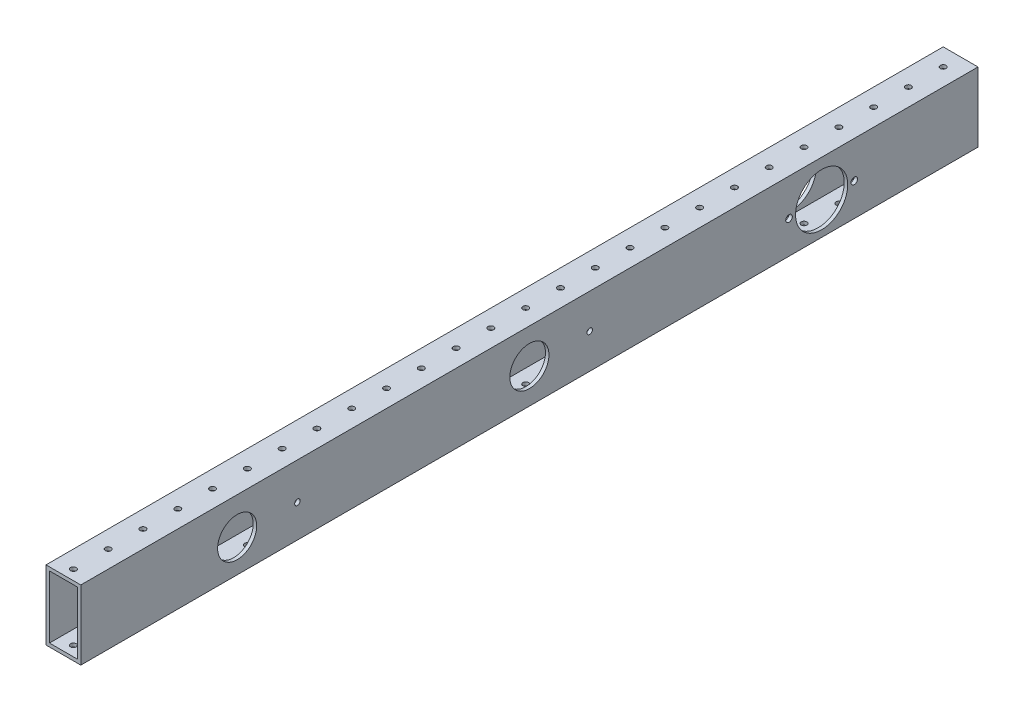
SolidWorks part; units mm, degrees
ref_plane "Alzado" through (0, 0, 0) normal (0, 0, 1) x (1, 0, 0)
ref_plane "Planta" through (0, 0, 0) normal (0, 1, 0) x (1, 0, 0)
ref_plane "Vista lateral" through (0, 0, 0) normal (1, 0, 0) x (0, 0, -1)
sketch "Croquis1" plane through (0, 0, 0) normal (0, 0, 1) x (1, 0, 0)
  line L1 (-12.7, 25.35) -> (12.7, 25.35)
  line L2 (-12.7, 25.35) -> (-12.7, -25.35)
  line L3 (-12.7, -25.35) -> (12.7, -25.35)
  line L4 (12.7, 25.35) -> (12.7, -25.35)
  line L5 (-12.7, 25.35) -> (12.7, -25.35) construction
  line L6 (-12.7, -25.35) -> (12.7, 25.35) construction
  line L7 (-10.16, 22.81) -> (10.16, 22.81)
  line L8 (-10.16, 22.81) -> (-10.16, -22.81)
  line L9 (-10.16, -22.81) -> (10.16, -22.81)
  line L10 (10.16, 22.81) -> (10.16, -22.81)
  line L11 (-10.16, 22.81) -> (10.16, -22.81) construction
  line L12 (-10.16, -22.81) -> (10.16, 22.81) construction
  point P0 (0, 0)
  point P6 (0, 0)
  dimension "D1" = 25.4
  dimension "D2" = 50.7
  dimension "D3" = 2.54
  dimension "D4" = 2.54
extrude "Saliente-Extruir1" add sketch "Croquis1" along normal blind 655
sketch "Croquis2" plane through (0, 25.35, 0) normal (0, 1, 0) x (1, 0, 0)
  line L0 (-12.7, 0) -> (12.7, 0)
  line L1 (12.7, 0) -> (0, 0)
  line L2 (0, 0) -> (0, -655)
  line L3 (12.7, -655) -> (-12.7, -655) construction
  circle A0 centre (0, -12.7) radius 2.07
  circle A1 centre (0, -38.1) radius 2.07
  circle A2 centre (0, -63.5) radius 2.07
  circle A3 centre (0, -88.9) radius 2.07
  circle A4 centre (0, -114.3) radius 2.07
  circle A5 centre (0, -139.7) radius 2.07
  circle A6 centre (0, -165.1) radius 2.07
  circle A7 centre (0, -190.5) radius 2.07
  circle A8 centre (0, -215.9) radius 2.07
  circle A9 centre (0, -241.3) radius 2.07
  circle A10 centre (0, -266.7) radius 2.07
  circle A11 centre (0, -292.1) radius 2.07
  circle A12 centre (0, -317.5) radius 2.07
  circle A13 centre (0, -342.9) radius 2.07
  circle A14 centre (0, -368.3) radius 2.07
  circle A15 centre (0, -393.7) radius 2.07
  circle A16 centre (0, -419.1) radius 2.07
  circle A17 centre (0, -444.5) radius 2.07
  circle A18 centre (0, -469.9) radius 2.07
  circle A19 centre (0, -495.3) radius 2.07
  circle A20 centre (0, -520.7) radius 2.07
  circle A21 centre (0, -546.1) radius 2.07
  circle A22 centre (0, -571.5) radius 2.07
  circle A23 centre (0, -596.9) radius 2.07
  circle A24 centre (0, -622.3) radius 2.07
  circle A25 centre (0, -647.7) radius 2.07
  dimension "D1" = 4.14
  dimension "D2" = 12.7
  dimension "D3" = 26
extrude "Cortar-Extruir1" cut sketch "Croquis2" against normal through all contours A0 | A1 | A2 | A3 | A4 | A5 | A6 | A7 | A8 | A9 | A10 | A11 | A12 | A13 | A14 | A15 | A16 | A17 | A18 | A19 | A20 | A21 | A22 | A23 | A24 | A25
sketch "Croquis3" plane through (-12.7, 0, 0) normal (-1, 0, 0) x (0, 0, 1)
  line L0 (0, 0) -> (327.5, 0)
  circle A0 centre (327.5, 0) radius 14.275
  dimension "D2" = 28.55
  dimension "D1" = 327.5
extrude "Cortar-Extruir2" cut sketch "Croquis3" against normal blind 700 contours A0
sketch "Croquis4" plane through (-12.7, 0, 0) normal (-1, 0, 0) x (0, 0, 1)
  circle A0 centre (303.9553, 0) radius 2.41
  dimension "D1" = 4.82
sketch "Croquis5" plane through (-12.7, 0, 0) normal (-1, 0, 0) x (0, 0, 1)
  line L0 (327.5, -25.35) -> (327.5926, 25.3498)
  line L2 (655, -25.35) -> (0, -25.35) construction
  line L3 (327.5926, 25.3498) -> (351.3125, 25.3498)
  line L4 (351.3125, 25.3498) -> (351.3125, -25.35)
  line L5 (351.3125, -25.35) -> (302.5949, -25.35)
  line L6 (302.5949, -25.35) -> (302.5949, 25.3498)
  line L7 (302.5949, 25.3498) -> (327.5926, 25.3498)
  line L8 (327.5, -25.35) -> (327.5463, -0.0001)
  line L9 (327.5463, -0.0001) -> (367.7335, -0.0735)
  line L10 (367.7335, -0.0735) -> (294.1923, 0.0608)
  circle A0 centre (351.3125, 0) radius 3.1556
sketch "Croquis6" plane through (-12.7, 0, 0) normal (-1, 0, 0) x (0, 0, 1)
  line L0 (82.895, 0) -> (478.5071, 0)
  circle A1 centre (303.6875, 0) radius 2.41
  circle A2 centre (351.3125, 0) radius 2.41
  circle A3 centre (354.42, 1.3931) radius 0.0224
  dimension "D1" = 4.82
sketch "Croquis7" plane through (-12.7, 0, 0) normal (-1, 0, 0) x (0, 0, 1)
  circle A0 centre (114.1451, -1.474) radius 14.2748
sketch "Croquis8" plane through (-12.7, 0, 0) normal (-1, 0, 0) x (0, 0, 1)
  circle A0 centre (114.1451, -1.474) radius 19.05
  circle A1 centre (540.8549, -1.474) radius 14.2748
  dimension "D1" = 28.5496
  dimension "D2" = 38.1
extrude "Cortar-Extruir5" cut sketch "Croquis8" against normal blind 700
sketch "Croquis9" plane through (-12.7, 0, 0) normal (-1, 0, 0) x (0, 0, 1)
  line L1 (655, 25.35) -> (0, 25.35) construction
  line L4 (655, -25.35) -> (0, -25.35) construction
  line L6 (158.1451, -3.494) -> (158.1451, -3.4693)
  line L7 (158.1451, 0.5693) -> (158.1451, 0.546)
  line L8 (158.1451, -1.45) -> (158.1451, -1.474)
  line L9 (156.1251, -1.474) -> (156.126, -1.474)
  line L10 (158.1451, 0.5693) -> (158.1451, 0.546)
  line L11 (540.8409, -1.4697) -> (540.8334, -1.494)
  line L12 (540.8334, -1.494) -> (480.5107, -1.494)
  line L13 (480.5107, -1.494) -> (480.5107, 25.35)
  line L14 (480.5107, 25.35) -> (489.2424, 25.35)
  line L15 (489.2424, 25.35) -> (489.2424, -25.35)
  line L16 (489.2424, -25.35) -> (496.8549, -1.45)
  line L17 (496.8549, -1.45) -> (489.2424, -25.35)
  line L18 (496.8549, -1.45) -> (496.8549, 25.35)
  line L19 (496.8549, 25.35) -> (496.8549, -25.35)
  line L20 (158.1451, 0.546) -> (158.1451, 0.5693)
  line L21 (160.1643, -1.474) -> (160.1651, -1.474)
  line L22 (158.1451, -1.474) -> (158.1451, -1.45)
  line L23 (158.1451, -3.4693) -> (158.1451, -3.494)
  arc A0 (156.1264, -1.4031) -> (156.126, -1.474) centre (158.1451, -1.45) ccw
  arc A1 (156.1264, -1.4031) -> (156.1251, -1.474) centre (158.1451, -1.474) ccw
  circle A2 centre (496.8409, -1.494) radius 2.02
  arc A3 (160.1643, -1.474) -> (160.1639, -1.4031) centre (158.1451, -1.45) ccw
  arc A4 (160.1651, -1.474) -> (160.1639, -1.4031) centre (158.1451, -1.474) ccw
  dimension "D1" = 4.04
  dimension "D2" = 4.04
  dimension "D3" = 44
sketch "Croquis10" plane through (12.7, 0, 0) normal (1, 0, 0) x (0, 0, -1)
  line L0 (-655, 25.35) -> (0, 25.35) construction
  circle A0 centre (-496.8549, -1.45) radius 2.02
  circle A1 centre (-540.8549, -1.474) radius 14.2748 construction
  dimension "D1" = 4.04
  dimension "D2" = 44
  dimension "D3" = 26.8
extrude "Cortar-Extruir7" cut sketch "Croquis10" against normal through all
sketch "Croquis12" plane through (12.7, 0, 0) normal (1, 0, 0) x (0, 0, -1)
  circle A0 centre (-283.5, 0) radius 2.02
  circle A1 centre (-327.5, 0) radius 14.275 construction
  dimension "D1" = 44
  dimension "D2" = 0
  dimension "D3" = 4.04
extrude "Cortar-Extruir8" cut sketch "Croquis12" against normal through all
sketch "Croquis14" plane through (-12.7, 0, 0) normal (-1, 0, 0) x (0, 0, 1)
  line L0 (0, 25.35) -> (0, -25.35) construction
  circle A1 centre (138, 0) radius 2.41
  dimension "D2" = 4.82
  dimension "D3" = 138
sketch "Croquis15" plane through (-12.7, 0, 0) normal (-1, 0, 0) x (0, 0, 1)
  circle A0 centre (137.9576, -1.474) radius 2.4095
  circle A1 centre (90.3326, -1.474) radius 2.413
extrude "Cortar-Extruir10" cut sketch "Croquis15" against normal through all
